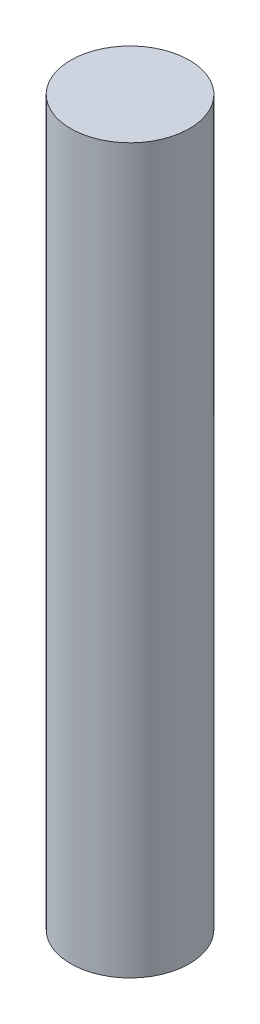
SolidWorks part; units mm, degrees
material "ABS PC"
ref_plane "Front Plane" through (0, 0, 0) normal (0, 0, 1) x (1, 0, 0)
ref_plane "Top Plane" through (0, 0, 0) normal (0, 1, 0) x (1, 0, 0)
ref_plane "Right Plane" through (0, 0, 0) normal (1, 0, 0) x (0, 0, -1)
sketch "Sketch1" plane through (0, 0, 0) normal (0, 1, 0) x (1, 0, 0)
  circle A0 centre (0, 0) radius 2.5
  dimension "D1" = 5
extrude "Boss-Extrude1" add sketch "Sketch1" along normal blind 30.48
